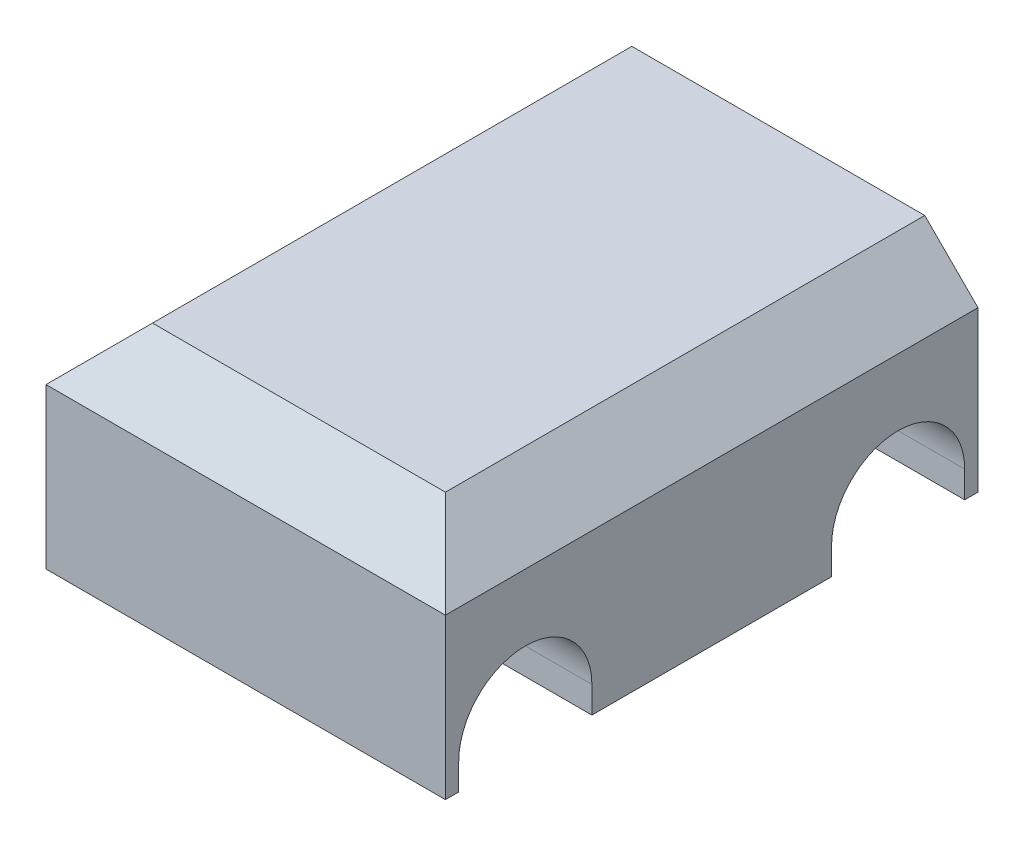
SolidWorks part; units mm, degrees
ref_plane "Front Plane" through (0, 0, 0) normal (0, 0, 1) x (1, 0, 0)
ref_plane "Top Plane" through (0, 0, 0) normal (0, 1, 0) x (1, 0, 0)
ref_plane "Right Plane" through (0, 0, 0) normal (1, 0, 0) x (0, 0, -1)
sketch "Sketch1" plane through (0, 0, 0) normal (0, 1, 0) x (1, 0, 0)
  line L1 (-75, 100) -> (75, 100)
  line L2 (-75, 100) -> (-75, -100)
  line L3 (-75, -100) -> (75, -100)
  line L4 (75, 100) -> (75, -100)
  line L5 (-75, 100) -> (75, -100) construction
  line L6 (-75, -100) -> (75, 100) construction
  point P0 (0, 0)
  dimension "D1" = 200
  dimension "D2" = 150
extrude "Boss-Extrude1" add sketch "Sketch1" along normal blind 80
ref_plane "Plane1" through (0, 0, 0) normal (0, 0, 1) x (1, 0, 0)
ref_plane "Plane2" through (0, 0, 0) normal (-1, 0, 0) x (0, 0, 1)
sketch "Sketch4" plane through (-75, 0, 0) normal (-1, 0, 0) x (0, 0, 1)
  line L0 (-70, 80) -> (-70, 0) construction
  line L1 (-100, 80) -> (100, 80) construction
  line L2 (-100, 0) -> (100, 0) construction
  line L3 (-100, 80) -> (-100, 0) construction
  line L4 (-100, 10) -> (100, 10) construction
  line L5 (100, 80) -> (100, 0) construction
  line L7 (-95, 10) -> (-45, 10)
  line L8 (-95, 10) -> (-95, -15)
  line L9 (-95, -15) -> (-45, -15)
  line L10 (-45, 10) -> (-45, -15)
  circle A0 centre (-70, 10) radius 25
  line M4 (-100, 0) -> (100, 0)
  dimension "D3" = 50
  dimension "D1" = 30
  dimension "D2" = 10
extrude "Cut-Extrude3" cut sketch "Sketch4" against normal blind 35 contours A0 L8 L9 M4 | A0 L8 M4 | L7 A0 M4 | L7 A0 | A0 L10 M4 | A0 L9 L10 M4 | A0 M4
mirror "Mirror1" about plane through (0, 0, 0) normal (0, 0, 1) of "Cut-Extrude3"
mirror "Mirror2" about plane through (0, 0, 0) normal (-1, 0, 0) of "Cut-Extrude3", "Mirror1"
chamfer "Chamfer1" distance 20 angle 45 3 edges at (75, 80, 0) (-75, 80, 0) (0, 80, 100)
